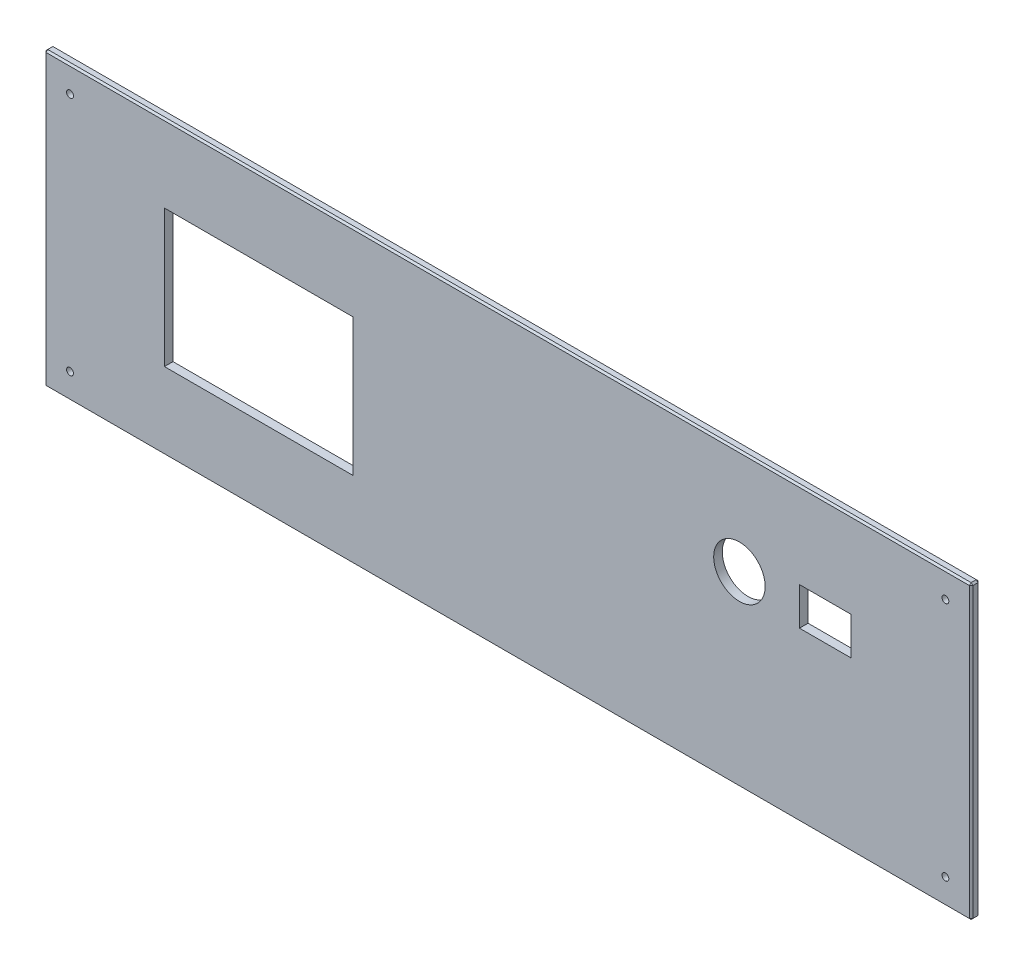
SolidWorks part; units mm, degrees
material "ABS"
ref_plane "Front Plane" through (0, 0, 0) normal (0, 0, 1) x (1, 0, 0)
ref_plane "Top Plane" through (0, 0, 0) normal (0, 1, 0) x (1, 0, 0)
ref_plane "Right Plane" through (0, 0, 0) normal (1, 0, 0) x (0, 0, -1)
sketch "Sketch1" plane through (0, 0, 0) normal (0, 0, 1) x (1, 0, 0)
  line L1 (0, 0) -> (540, 0)
  line L2 (0, 0) -> (0, 170)
  line L3 (0, 170) -> (540, 170)
  line L4 (540, 0) -> (540, 170)
  dimension "D1" = 540
  dimension "D2" = 170
extrude "Boss-Extrude1" add sketch "Sketch1" along normal blind 5
chamfer "Chamfer1" distance 1 angle 45 12 edges at (270, 0, 0) (540, 85, 0) (270, 170, 0) (0, 85, 0) (270, 170, 5) (0, 170, 2.5) (0, 85, 5) (0, 0, 2.5) (270, 0, 5) (540, 0, 2.5) (540, 85, 5) (540, 170, 2.5)
sketch "Sketch2" plane through (0, 0, 5) normal (0, 0, 1) x (1, 0, 0)
  line L0 (1, 170) -> (539, 170) construction
  line L1 (15, 155) -> (525, 155) construction
  line L2 (15, 155) -> (15, 15) construction
  line L3 (15, 15) -> (525, 15) construction
  line L4 (525, 155) -> (525, 15) construction
  line L5 (540, 169) -> (540, 1) construction
  line L6 (539, 0) -> (1, 0) construction
  line L7 (0, 1) -> (0, 169) construction
  circle A0 centre (525, 155) radius 2
  circle A1 centre (525, 15) radius 2
  circle A2 centre (15, 155) radius 2
  circle A3 centre (15, 15) radius 2
  dimension "D5" = 4
  dimension "D6" = 4
  dimension "D7" = 4
  dimension "D8" = 4
  dimension "D1" = 15
  dimension "D2" = 15
  dimension "D3" = 15
  dimension "D4" = 15
extrude "Cut-Extrude1" cut sketch "Sketch2" against normal blind 5
sketch "Sketch3" plane through (0, 0, 0) normal (0, 0, -1) x (-1, 0, 0)
  line L0 (-539, 85) -> (0, 85) construction
  line L1 (-539, 169) -> (-539, 1) construction
  line L2 (-270, 169) -> (-270, 0) construction
  line L3 (-1, 169) -> (-539, 169) construction
  line L4 (-1, 0) -> (-539, 0) construction
  line L5 (0, 169) -> (0, 1) construction
  line L6 (-440, 109) -> (-405, 109) construction
  line L7 (-470, 120) -> (-440, 120)
  line L8 (-470, 120) -> (-470, 98)
  line L9 (-470, 98) -> (-440, 98)
  line L10 (-440, 120) -> (-440, 98)
  line L11 (-180, 125) -> (-70, 125)
  line L12 (-180, 125) -> (-180, 45)
  line L13 (-180, 45) -> (-70, 45)
  line L14 (-70, 125) -> (-70, 45)
  circle A0 centre (-405, 109) radius 15
  dimension "D5" = 30
  dimension "D1" = 22
  dimension "D2" = 35
  dimension "D3" = 200
  dimension "D4" = 30
  dimension "D6" = 135
  dimension "D7" = 110
  dimension "D8" = 80
  dimension "D9" = 40
  dimension "D10" = 200
extrude "Cut-Extrude2" cut sketch "Sketch3" against normal blind 10 contours L11 L14 L13 L12
